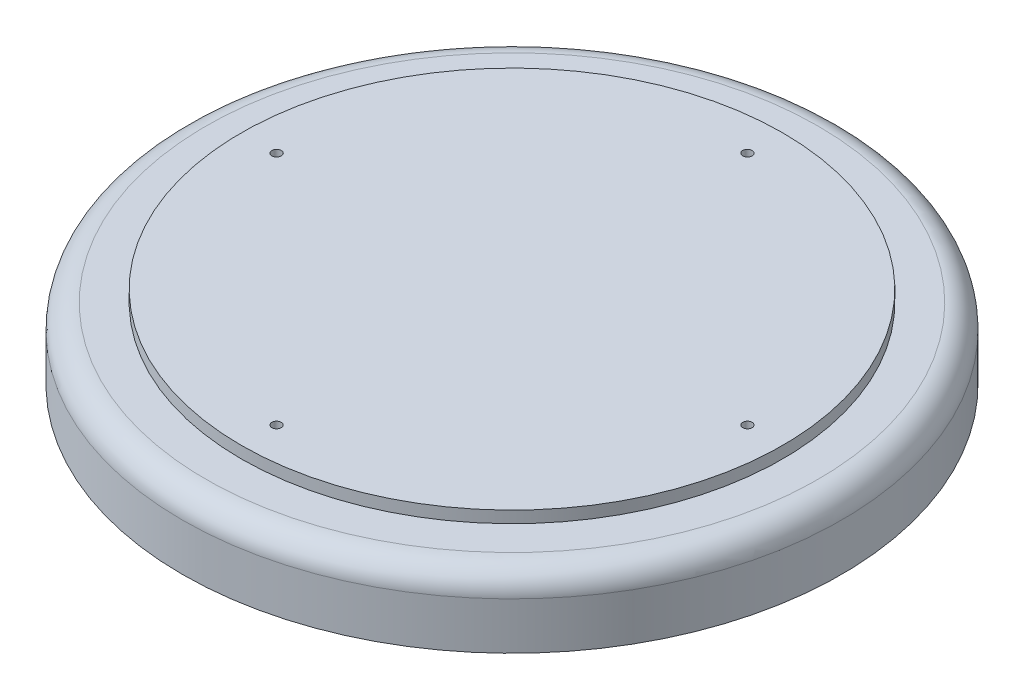
SolidWorks part; units mm, degrees
ref_plane "Front Plane" through (0, 0, 0) normal (0, 0, 1) x (1, 0, 0)
ref_plane "Top Plane" through (0, 0, 0) normal (0, 1, 0) x (1, 0, 0)
ref_plane "Right Plane" through (0, 0, 0) normal (1, 0, 0) x (0, 0, -1)
sketch "Sketch1" plane through (0, 0, 0) normal (0, 1, 0) x (1, 0, 0)
  circle A0 centre (0, 0) radius 146.05
  dimension "D1" = 292.1
extrude "Boss-Extrude1" add sketch "Sketch1" along normal blind 6.35
sketch "Sketch2" plane through (0, 0, 0) normal (0, -1, 0) x (1, 0, 0)
  circle A0 centre (0, 0) radius 177.8
  circle A1 centre (0, 0) radius 146.05 construction
  dimension "D1" = 31.75
extrude "Boss-Extrude2" add sketch "Sketch2" along normal blind 38.1
sketch "Sketch3" plane through (0, -38.1, 0) normal (0, -1, 0) x (1, 0, 0)
  circle A0 centre (0, 0) radius 174.625
  circle A1 centre (0, 0) radius 177.8 construction
  dimension "D1" = 3.175
extrude "Cut-Extrude2" cut sketch "Sketch3" against normal offset from surface (34.925 mm away) 3.175 up to face at (0, 0, -146.05)
fillet "Fillet2" radius 12.7 1 edges at (0, -3.175, -174.625)
fillet "Fillet3" radius 12.7 1 edges at (0, 0, -177.8)
sketch "Sketch4" plane through (0, 6.35, 0) normal (0, 1, 0) x (1, 0, 0)
  line L0 (-127, 0) -> (-146.05, 0) construction
  line L1 (0, 127) -> (0, 146.05) construction
  line L2 (127, 0) -> (146.05, 0) construction
  line L3 (0, -127) -> (0, -146.05) construction
  circle A0 centre (0, 127) radius 2.54
  circle A1 centre (127, 0) radius 2.54
  circle A2 centre (-127, 0) radius 2.54
  circle A3 centre (0, -127) radius 2.54
  circle A5 centre (0, 0) radius 146.05 construction
  dimension "D5" = 5.08
  dimension "D6" = 5.08
  dimension "D7" = 5.08
  dimension "D8" = 5.08
  dimension "D1" = 19.05
  dimension "D2" = 19.05
  dimension "D3" = 19.05
  dimension "D4" = 19.05
extrude "Cut-Extrude3" cut sketch "Sketch4" against normal up to surface (9.525 mm away) up to face at (0, -3.175, -161.925)
